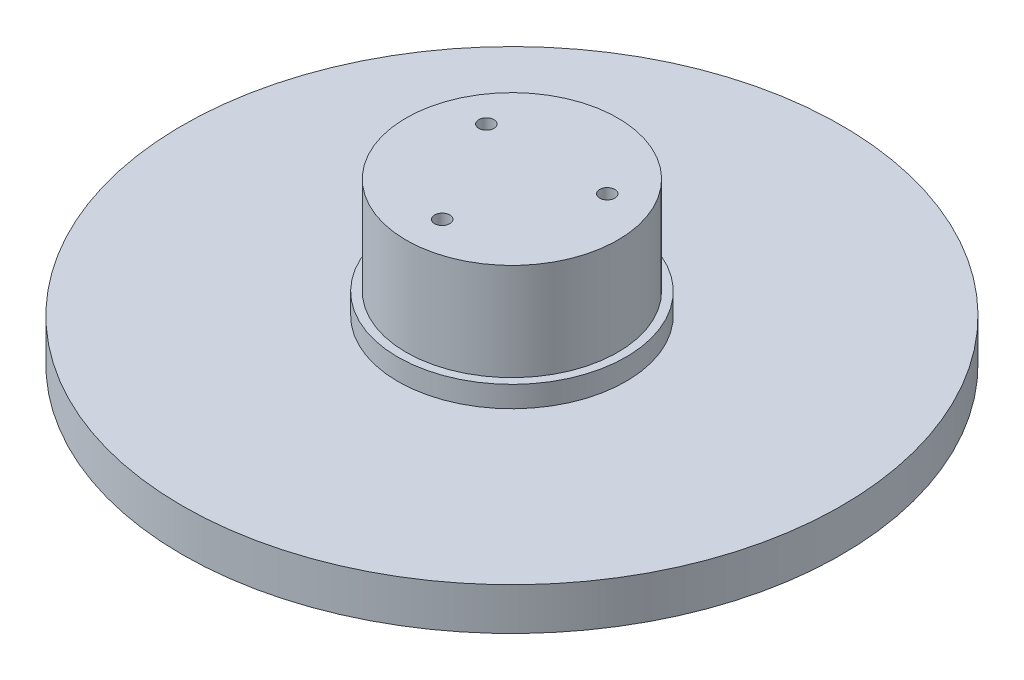
SolidWorks part; units mm, degrees
ref_plane "Front Plane" through (0, 0, 0) normal (0, 0, 1) x (1, 0, 0)
ref_plane "Top Plane" through (0, 0, 0) normal (0, 1, 0) x (1, 0, 0)
ref_plane "Right Plane" through (0, 0, 0) normal (1, 0, 0) x (0, 0, -1)
sketch "Sketch1" plane through (0, 0, 0) normal (0, 1, 0) x (1, 0, 0)
  circle A0 centre (0, 0) radius 78
  dimension "D1" = 156
extrude "Boss-Extrude1" add sketch "Sketch1" along normal blind 10
sketch "Sketch2" plane through (0, 10, 0) normal (0, 1, 0) x (1, 0, 0)
  circle A0 centre (0, 0) radius 27
  dimension "D1" = 54
extrude "Boss-Extrude2" add sketch "Sketch2" along normal blind 5
sketch "Sketch3" plane through (0, 15, 0) normal (0, 1, 0) x (1, 0, 0)
  circle A0 centre (0, 0) radius 25.05
  dimension "D1" = 50.1
extrude "Boss-Extrude3" add sketch "Sketch3" along normal blind 23
sketch "Sketch6" plane through (0, 0, 0) normal (0, -1, 0) x (-1, 0, 0)
  line L0 (-14.2981, 8.255) -> (0, 0) construction
  line L1 (0, 0) -> (14.2981, 8.255) construction
  line L3 (0, 0) -> (0, -16.51) construction
  point P0 (0, -16.51)
  point P2 (-14.2981, 8.255)
  point P4 (14.2981, 8.255)
  dimension "D1" = 16.51
  dimension "D2" = 120
  dimension "D3" = 120
hole_wizard "CBORE for M3 SHCS1" positions "Sketch6" profile "Sketch5" counterbore size "M3" standard "ANSI Metric" end condition through all
sketch "Sketch5" plane through (0, 0, 16.51) normal (1, 0, 0) x (0, 0, -1)
  line L0 (0, 0) -> (0, 38)
  line L1 (0, 38) -> (1.8, 38)
  line L3 (1.8, 38) -> (1.8, 23)
  line L4 (3.25, 23) -> (1.8, 23)
  line L5 (3.25, 23) -> (3.25, 0.025)
  line L6 (3.25, 0.025) -> (3.275, 0)
  line L7 (3.275, 0) -> (0, 0)
  line L8 (-3.25, 0.025) -> (-3.275, 0) construction
  line L11 (0, -6.35) -> (0, 107.95) construction
  dimension "Thru Hole Dia." = 3.6
  dimension "Thru Hole Depth" = 38
  dimension "C'Bore Dia." = 6.5
  dimension "C'Bore Depth" = 23
  dimension "Near C'Sink Dia." = 6.55
  dimension "Near C'Sink Angle" = 90
